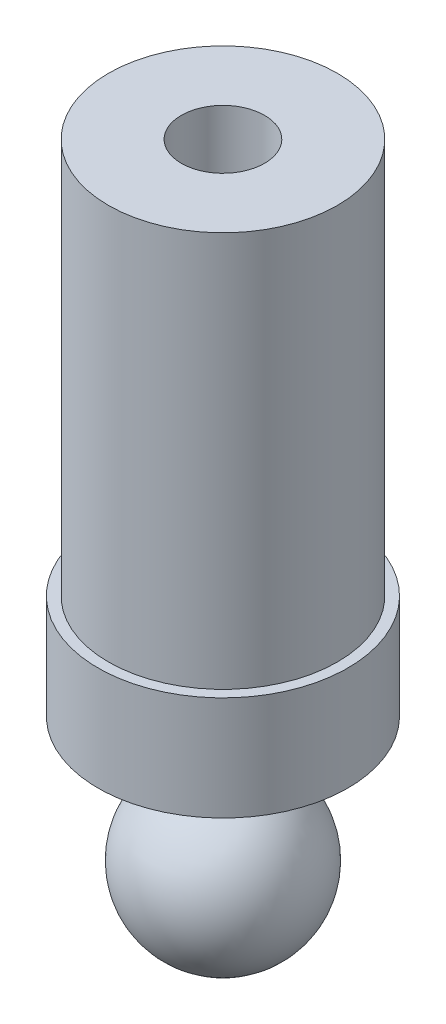
SolidWorks part; units mm, degrees
ref_plane "Front Plane" through (0, 0, 0) normal (0, 0, 1) x (1, 0, 0)
ref_plane "Top Plane" through (0, 0, 0) normal (0, 1, 0) x (1, 0, 0)
ref_plane "Right Plane" through (0, 0, 0) normal (1, 0, 0) x (0, 0, -1)
sketch "Sketch1" plane through (0, 0, 0) normal (0, 1, 0) x (1, 0, 0)
  circle A0 centre (0, 0) radius 6
  dimension "D1" = 12
extrude "Boss-Extrude1" add sketch "Sketch1" along normal blind 45
sketch "Sketch2" plane through (0, 0, 0) normal (0, -1, 0) x (1, 0, 0)
  circle A0 centre (0, 0) radius 4.5
  circle A1 centre (0, 0) radius 6
  circle A2 centre (0, 0) radius 6
  dimension "D1" = 0
  dimension "D2" = 1.5
ref_plane "Plane1" through (0, 5, 0) normal (0, 1, 0) x (1, 0, 0)
sketch "Sketch4" plane through (0, 5, 0) normal (0, 1, 0) x (1, 0, 0)
  circle A0 centre (0, 0) radius 6 construction
  circle A1 centre (0, 0) radius 6
  circle A2 centre (0, 0) radius 5.5
  dimension "D1" = 0.5
sketch "Sketch5" plane through (0, 45, 0) normal (0, 1, 0) x (1, 0, 0)
  circle A0 centre (0, 0) radius 2
  dimension "D1" = 4
ref_plane "Plane2" through (0, 53, 0) normal (0, 1, 0) x (1, 0, 0)
sketch "Sketch6" plane through (0, 53, 0) normal (0, 1, 0) x (1, 0, 0)
  line L0 (-4, 0) -> (4, 0) construction
  line L1 (-4, 0) -> (4, 0)
  arc A0 (-4, 0) -> (4, 0) centre (0, 0) cw
  point P2 (0, 0)
  point P3 (0, 0)
  dimension "D1" = 8
ref_plane "Plane3" through (0, 24, 0) normal (0, 1, 0) x (1, 0, 0)
sketch "Sketch7" plane through (0, 24, 0) normal (0, 1, 0) x (1, 0, 0)
  line L0 (-7.5, 7.5) -> (7.5, -7.5) construction
  line L1 (-7.5, 7.5) -> (7.5, 7.5)
  line L2 (-7.5, 7.5) -> (-7.5, -7.5)
  line L3 (-7.5, -7.5) -> (7.5, -7.5)
  line L4 (7.5, 7.5) -> (7.5, -7.5)
  point P4 (0, 0)
  dimension "D1" = 15
  dimension "D2" = 15
extrude "Cut-Extrude5" cut sketch "Sketch7" along normal blind 25
extrude "Cut-Extrude6" cut sketch "Sketch4" along normal blind 38
extrude "Cut-Extrude7" cut sketch "Sketch5" against normal blind 56 contours A0
sketch "Sketch8" plane through (0, 0, 0) normal (0, -1, 0) x (1, 0, 0)
  circle A0 centre (0, 0) radius 2 construction
  circle A1 centre (0, 0) radius 2
extrude "Boss-Extrude2" add sketch "Sketch8" along normal blind 3 separate body
ref_plane "Plane4" through (0, -6, 0) normal (0, 1, 0) x (1, 0, 0)
sketch "Sketch9" plane through (0, -6, 0) normal (0, 1, 0) x (1, 0, 0)
  line L0 (-4, 0) -> (4, 0) construction
  line L1 (-4, 0) -> (4, 0)
  arc A0 (4, 0) -> (-4, 0) centre (0, 0) ccw construction
  arc A1 (4, 0) -> (-4, 0) centre (0, 0) ccw
revolve "Revolve2" add sketch "Sketch9" angle 360 about L1
